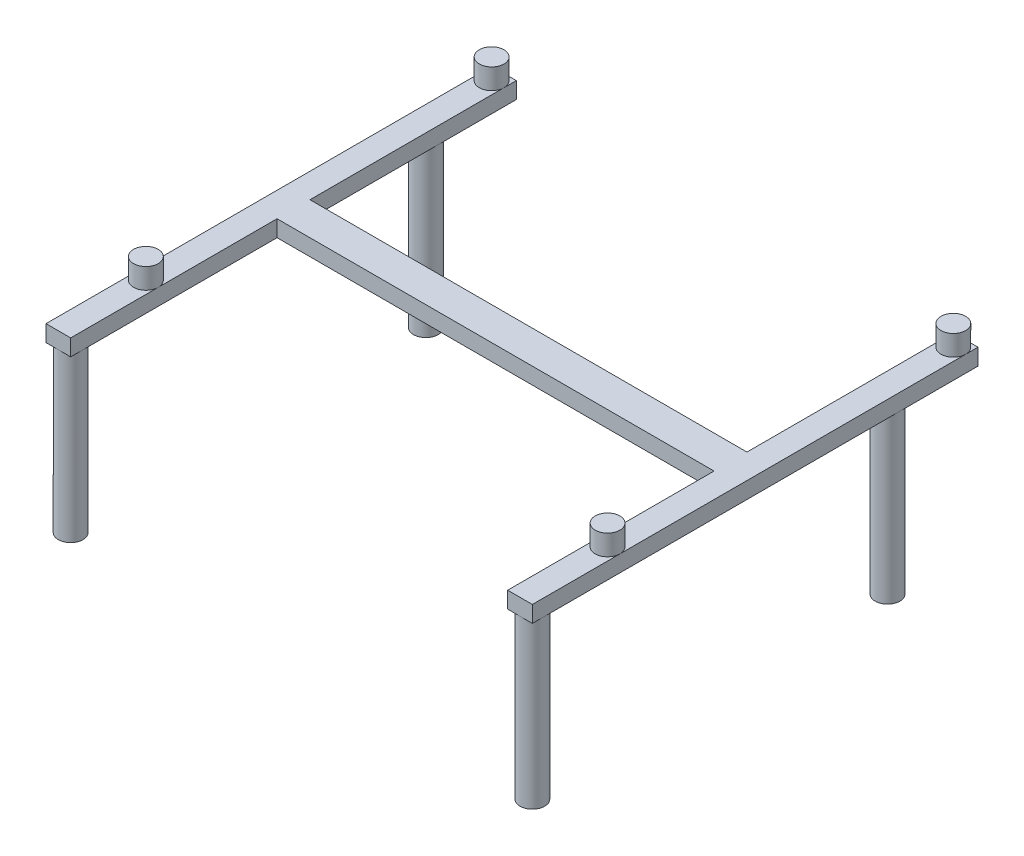
SolidWorks part; units mm, degrees
ref_plane "前视基准面" through (0, 0, 0) normal (0, 0, 1) x (1, 0, 0)
ref_plane "上视基准面" through (0, 0, 0) normal (0, 1, 0) x (1, 0, 0)
ref_plane "右视基准面" through (0, 0, 0) normal (1, 0, 0) x (0, 0, -1)
other "Configuration Table"
sketch "草图1" plane through (0, 0, 0) normal (0, 1, 0) x (1, 0, 0)
  line L0 (0, 43.18) -> (0, 0) construction
  line L1 (56.13, 43.18) -> (0, 43.18) construction
  line L2 (56.13, 0) -> (56.13, 43.18) construction
  line L3 (28.065, 43.18) -> (28.065, 39.1656) construction
  line L4 (56.13, 43.18) -> (0, 43.18) construction
  circle A0 centre (0, 0) radius 1.5
  circle A1 centre (0, 43.18) radius 1.5
  circle A2 centre (56.13, 43.18) radius 1.5
  circle A3 centre (56.13, 0) radius 1.5
  point P10 (28.065, 43.18)
  dimension "D1" = 3
  dimension "D2" = 3
  dimension "D4" = 3
  dimension "D6" = 3
  dimension "D3" = 43.18
  dimension "D5" = 56.13
  dimension "D7" = 43.18
extrude "凸台-拉伸1" add sketch "草图1" along normal blind 20
sketch "草图2" plane through (0, 20, 0) normal (0, 1, 0) x (1, 0, 0)
  line L0 (-1.5, 52.68) -> (-1.5, -1.5)
  line L1 (-1.5, -1.5) -> (1.5, -1.5)
  line L3 (1.5, 52.68) -> (-1.5, 52.68)
  line L5 (54.63, -1.5) -> (57.63, -1.5)
  line L6 (57.63, -1.5) -> (57.63, 52.68)
  line L7 (57.63, 52.68) -> (54.63, 52.68)
  line L8 (1.5, 27.59) -> (54.63, 27.59)
  line L10 (54.63, 23.59) -> (1.5, 23.59)
  line L13 (54.63, 52.68) -> (54.63, 27.59)
  line L14 (1.5, 52.68) -> (1.5, 27.59)
  line L15 (1.5, 23.59) -> (1.5, -1.5)
  line L16 (54.63, 23.59) -> (54.63, -1.5)
  circle A0 centre (0, 43.18) radius 1.5 construction
  circle A1 centre (0, 0) radius 1.5 construction
  circle A2 centre (56.13, 43.18) radius 1.5 construction
  circle A3 centre (56.13, 0) radius 1.5 construction
  point P22 (-1.5, 25.59)
  dimension "D1" = 9.5
  dimension "D2" = 9.5
  dimension "D3" = 4
  dimension "D4" = 2
extrude "凸台-拉伸2" add sketch "草图2" along normal blind 2
sketch "草图4" plane through (0, 22, 0) normal (0, 1, 0) x (1, 0, 0)
  line L0 (1.5, 27.59) -> (1.5, 52.68) construction
  line L1 (28.065, 27.59) -> (28.065, 23.59) construction
  line L2 (0, -1.5) -> (0, 52.68) construction
  line L3 (-1.5, -1.5) -> (1.5, -1.5) construction
  line L4 (1.5, 52.68) -> (-1.5, 52.68) construction
  line L7 (54.63, 27.59) -> (1.5, 27.59) construction
  circle A0 centre (0, 51.18) radius 1.5
  circle A1 centre (0, 9.143) radius 1.5
  circle A2 centre (56.13, 9.143) radius 1.5
  circle A3 centre (56.13, 51.18) radius 1.5
  point P16 (28.065, 27.59)
  dimension "D1" = 42.037
extrude "凸台-拉伸3" add sketch "草图4" along normal blind 2.5
